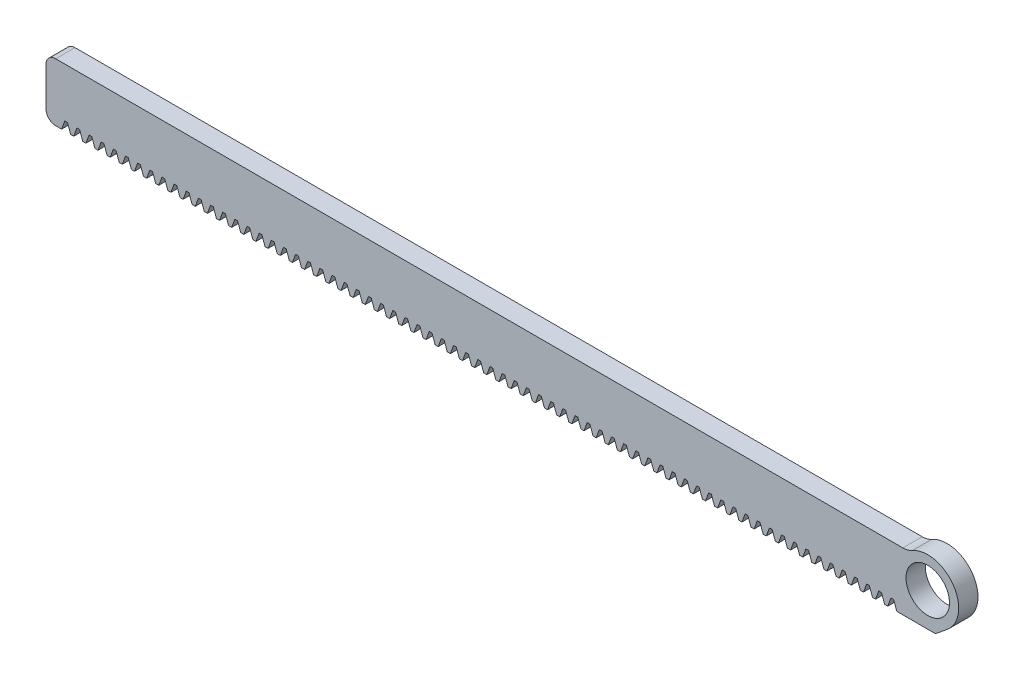
SolidWorks part; units mm, degrees
material "PC High Viscosity"
ref_plane "Front Plane" through (0, 0, 0) normal (0, 0, 1) x (1, 0, 0)
ref_plane "Top Plane" through (0, 0, 0) normal (0, 1, 0) x (1, 0, 0)
ref_plane "Right Plane" through (0, 0, 0) normal (1, 0, 0) x (0, 0, -1)
sketch "Sketch1" plane through (0, 0, 0) normal (0, 0, 1) x (1, 0, 0)
  line L2 (0, 0) -> (0, 38.1)
  line L3 (0, 38.1) -> (41.1221, 38.1)
  line L8 (41.1221, 38.1) -> (549.2313, 38.1)
  line L9 (0, 0) -> (584.2, 0)
  line L19 (584.6795, 2.564) -> (584.6795, 10.0162) construction
  line L20 (584.6795, 10.0162) -> (0, 10.0162) construction
  line L21 (0, 10.0162) -> (0, 0) construction
  line L28 (560.3214, 25.4803) -> (569.7207, 77.8858) construction
  line L29 (588.5193, 77.8858) -> (597.9186, 25.4803) construction
  line L30 (549.2313, 38.1) -> (562.776, 38.1)
  line L32 (591.9998, 6.392) -> (584.2, 0)
  arc A17 (588.5193, 77.8858) -> (569.7207, 77.8858) centre (579.12, 76.2) ccw construction
  arc A18 (560.3214, 25.4803) -> (597.9186, 25.4803) centre (579.12, 22.1086) ccw construction
  circle A19 centre (579.12, 22.1086) radius 14.2875
  arc A21 (590.2175, 39.1306) -> (569.0622, 39.7649) centre (579.12, 22.1086) ccw
  arc A23 (562.776, 38.1) -> (569.0622, 39.7649) centre (562.776, 50.8) ccw
  arc A24 (566.5829, 38.1) -> (596.6937, 32.3101) centre (579.12, 22.1086) ccw construction
  arc A25 (590.2175, 39.1306) -> (569.0622, 39.7649) centre (579.12, 22.1086) ccw construction
  circle A26 centre (579.12, 22.1086) radius 20.32
  point P48 (579.12, 76.2)
  dimension "D12" = 28.575
  dimension "D4" = 40.64
  dimension "D6" = 12.7
  dimension "D2" = 38.1
  dimension "D7" = 76.2
  dimension "D3" = 579.12
  dimension "D5" = 584.2
extrude "Boss-Extrude1" add sketch "Sketch1" along normal blind 12.7
fillet "Fillet2" radius 6.35 2 edges at (0, 38.1, 6.35) (0, 0, 6.35)
sketch "Sketch2" plane through (0, 0, 12.7) normal (0, 0, 1) x (1, 0, 0)
  line L0 (558.8, 0) -> (-76.2, 0)
  line L1 (-76.2, 0) -> (-76.2, 5.715)
  line L2 (-76.2, 5.715) -> (558.8, 5.715)
  line L3 (558.8, 5.715) -> (558.8, 0)
  line L5 (557.8755, 2.54) -> (549.711, 2.54) construction
  line L6 (558.8, 0) -> (556.7199, 5.715)
  line L8 (552.8688, 0) -> (558.8, 0)
  line L10 (556.7199, 5.715) -> (554.9488, 5.715)
  line L11 (558.8, 0) -> (552.8688, 0)
  line L12 (552.8688, 0) -> (554.9488, 5.715)
  line L13 (554.9488, 5.715) -> (556.7199, 5.715)
  line L14 (558.8, 0) -> (552.8688, 0)
  line L15 (554.9488, 5.715) -> (556.7199, 5.715)
  line L16 (558.8, 0) -> (552.8688, 0)
  line L17 (552.8688, 0) -> (558.8, 0)
  line L19 (556.7199, 5.715) -> (554.9488, 5.715) construction
  line L20 (552.8688, 0) -> (558.8, 0) construction
  line L23 (0, 0) -> (584.2, 0) construction
  point P8 (553.7932, 2.54)
  point P16 (557.8755, 2.54)
  dimension "D1" = 70
  dimension "D2" = 2.54
  dimension "D3" = 3.175
  dimension "D4" = 70
  dimension "D5" = 1.7711
  dimension "D6" = 3.976
  dimension "D7" = 635
extrude "Cut-Extrude1" cut sketch "Sketch2" against normal through all contours L12 L0 L8 L6 L2
pattern_linear "LPattern1" count 69 spacing 7.9796 along (-1, 0, 0) of "Cut-Extrude1"
equation "\"D11@Sketch1\"=(24*5mm)/pi"
equation "\"D10@Sketch1\"=(12*5mm)/pi"
equation "\"D13@Sketch1\"=(40*5mm)-0.005"
